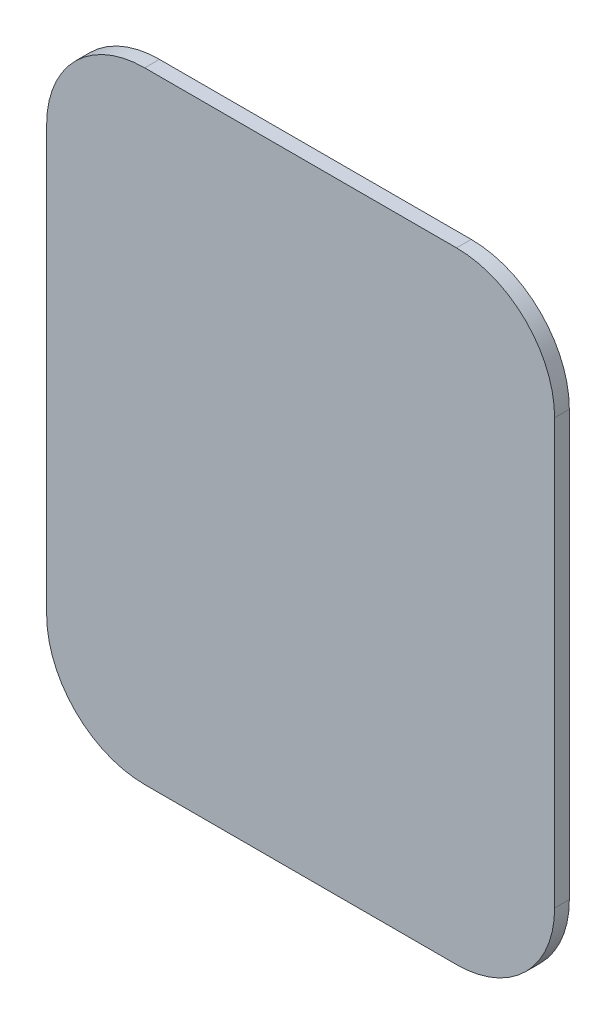
SolidWorks part; units mm, degrees
ref_plane "前视基准面" through (0, 0, 0) normal (0, 0, 1) x (1, 0, 0)
ref_plane "上视基准面" through (0, 0, 0) normal (0, 1, 0) x (1, 0, 0)
ref_plane "右视基准面" through (0, 0, 0) normal (1, 0, 0) x (0, 0, -1)
sketch "草图1" plane through (0, 0, 0) normal (0, 0, 1) x (1, 0, 0)
  line L1 (-51.8, 63.3) -> (51.8, 63.3)
  line L2 (-51.8, 63.3) -> (-51.8, -63.3)
  line L3 (-51.8, -63.3) -> (51.8, -63.3)
  line L4 (51.8, 63.3) -> (51.8, -63.3)
  line L5 (-51.8, 63.3) -> (51.8, -63.3) construction
  line L6 (-51.8, -63.3) -> (51.8, 63.3) construction
  point P0 (0, 0)
  dimension "D1" = 103.6
  dimension "D2" = 126.6
extrude "凸台-拉伸1" add sketch "草图1" along normal blind 3
fillet "圆角1" radius 20 4 edges at (-51.8, 63.3, 1.5) (-51.8, -63.3, 1.5) (51.8, -63.3, 1.5) (51.8, 63.3, 1.5)
